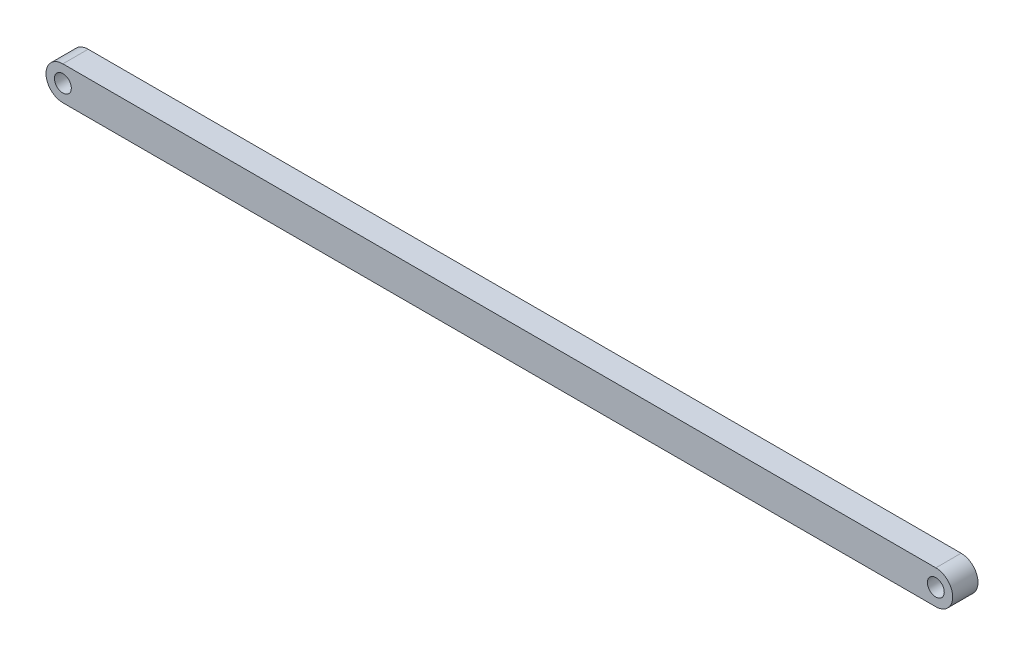
SolidWorks part; units mm, degrees
ref_plane "Front Plane" through (0, 0, 0) normal (0, 0, 1) x (1, 0, 0)
ref_plane "Top Plane" through (0, 0, 0) normal (0, 1, 0) x (1, 0, 0)
ref_plane "Right Plane" through (0, 0, 0) normal (1, 0, 0) x (0, 0, -1)
sketch "Sketch1" plane through (0, 0, 0) normal (0, 0, 1) x (1, 0, 0)
  line L0 (0, 0) -> (103.5, 0) construction
  line L1 (0, 2) -> (103.5, 2)
  line L2 (0, -2) -> (103.5, -2)
  arc A0 (0, 2) -> (0, -2) centre (0, 0) ccw
  arc A1 (103.5, -2) -> (103.5, 2) centre (103.5, 0) ccw
  circle A2 centre (0, 0) radius 1
  circle A3 centre (103.5, 0) radius 1
  point P3 (51.75, 0)
  dimension "D2" = 2
  dimension "D3" = 2
  dimension "D4" = 2
  dimension "D1" = 103.5
extrude "Boss-Extrude1" add sketch "Sketch1" along normal blind 3
